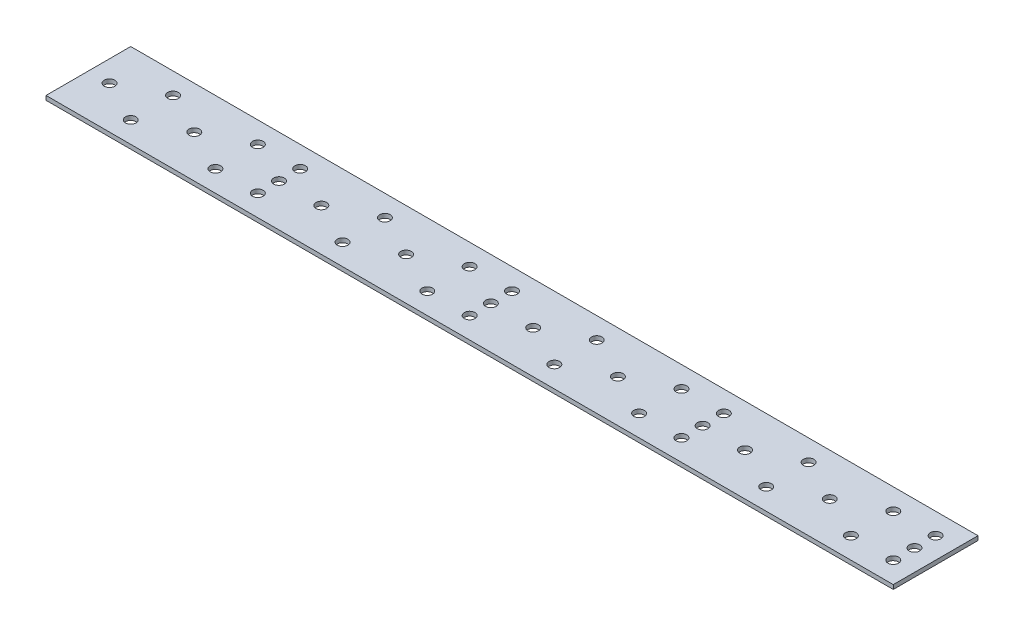
SolidWorks part; units mm, degrees
ref_plane "Спереди" through (0, 0, 0) normal (0, 0, 1) x (1, 0, 0)
ref_plane "Сверху" through (0, 0, 0) normal (0, 1, 0) x (1, 0, 0)
ref_plane "Справа" through (0, 0, 0) normal (1, 0, 0) x (0, 0, -1)
sketch "Эскиз1" plane through (0, 0, 0) normal (0, 1, 0) x (1, 0, 0)
  line L0 (-200, 0) -> (200, 0) construction
  line L1 (200, 20) -> (-200, 20)
  line L2 (200, 20) -> (200, -20)
  line L3 (200, -20) -> (-200, -20)
  line L4 (-200, 20) -> (-200, -20)
  line L5 (200, 20) -> (-200, -20) construction
  line L6 (200, -20) -> (-200, 20) construction
  line L7 (-190, 0) -> (-90, 0) construction
  circle A0 centre (-190, 0) radius 2.5
  circle A1 centre (-170, 10) radius 2.5
  circle A2 centre (-170, -10) radius 2.5
  circle A3 centre (-150, 0) radius 2.5
  circle A4 centre (-130, 10) radius 2.5
  circle A5 centre (-130, -10) radius 2.5
  circle A6 centre (-110, 10) radius 2.5
  circle A7 centre (-110, 0) radius 2.5
  circle A8 centre (-110, -10) radius 2.5
  circle A9 centre (-90, 0) radius 2.5
  circle A10 centre (-70, 10) radius 2.5
  circle A11 centre (-70, -10) radius 2.5
  circle A12 centre (-50, 0) radius 2.5
  circle A13 centre (-30, 10) radius 2.5
  circle A14 centre (-30, -10) radius 2.5
  circle A15 centre (-10, -10) radius 2.5
  circle A16 centre (-10, 0) radius 2.5
  circle A17 centre (-10, 10) radius 2.5
  circle A18 centre (10, 0) radius 2.5
  circle A19 centre (30, 10) radius 2.5
  circle A20 centre (30, -10) radius 2.5
  circle A21 centre (50, 0) radius 2.5
  circle A22 centre (70, 10) radius 2.5
  circle A23 centre (70, -10) radius 2.5
  circle A24 centre (90, -10) radius 2.5
  circle A25 centre (90, 0) radius 2.5
  circle A26 centre (90, 10) radius 2.5
  circle A27 centre (110, 0) radius 2.5
  circle A28 centre (130, 10) radius 2.5
  circle A29 centre (130, -10) radius 2.5
  circle A30 centre (150, 0) radius 2.5
  circle A31 centre (170, 10) radius 2.5
  circle A32 centre (170, -10) radius 2.5
  circle A33 centre (190, -10) radius 2.5
  circle A34 centre (190, 0) radius 2.5
  circle A35 centre (190, 10) radius 2.5
  point P0 (0, 0)
  dimension "D3" = 5
  dimension "D6" = 5
  dimension "D8" = 5
  dimension "D10" = 5
  dimension "D12" = 5
  dimension "D13" = 5
  dimension "D1" = 40
  dimension "D2" = 400
  dimension "D4" = 10
  dimension "D5" = 20
  dimension "D7" = 20
  dimension "D9" = 20
  dimension "D11" = 20
  dimension "D14" = 20
  dimension "D16" = 100
  dimension "D15" = 4
extrude "Бобышка-Вытянуть1" add sketch "Эскиз1" along normal blind 2
equation "\"D5@Эскиз1\"=\"D1@Эскиз1\"/2"
equation "\"D6@Эскиз1\"=\"D3@Эскиз1\""
equation "\"D8@Эскиз1\"=\"D3@Эскиз1\""
equation "\"D9@Эскиз1\"=\"D7@Эскиз1\""
equation "\"D10@Эскиз1\"=\"D6@Эскиз1\""
equation "\"D11@Эскиз1\"=\"D9@Эскиз1\""
equation "\"D12@Эскиз1\"=\"D10@Эскиз1\""
equation "\"D13@Эскиз1\"=\"D10@Эскиз1\""
equation "\"D14@Эскиз1\"=\"D11@Эскиз1\""
